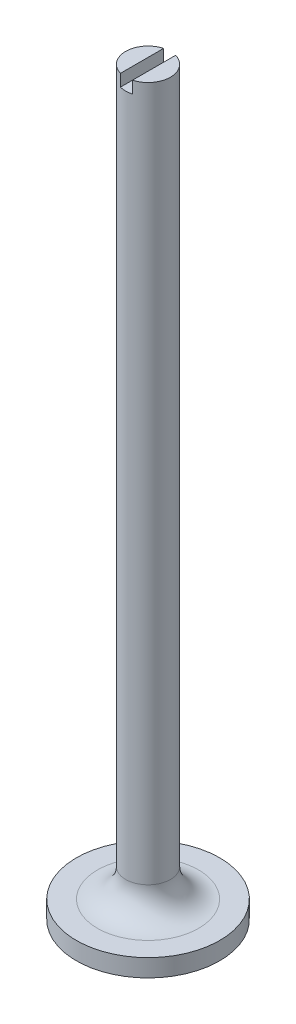
SolidWorks part; units mm, degrees
material "AISI 316 Annealed Stainless Steel Bar (SS)"
ref_plane "Front Plane" through (0, 0, 0) normal (0, 0, 1) x (1, 0, 0)
ref_plane "Top Plane" through (0, 0, 0) normal (0, 1, 0) x (1, 0, 0)
ref_plane "Right Plane" through (0, 0, 0) normal (1, 0, 0) x (0, 0, -1)
sketch "Sketch1" plane through (0, 0, 0) normal (0, 0, 1) x (1, 0, 0)
  line L0 (0, -31.8317) -> (0, 0) construction
  line L1 (0, 0) -> (10.16, 0)
  line L2 (10.16, 0) -> (10.16, 2.5)
  line L4 (3.175, 2.5) -> (3.175, 105)
  line L5 (3.175, 105) -> (0, 105)
  line L7 (0, 105) -> (0, 0)
  line L8 (10.16, 2.5) -> (3.175, 2.5)
  dimension "D1" = 10.16
  dimension "D2" = 3.175
  dimension "D3" = 2.5
  dimension "D4" = 105
revolve "Revolve1" add sketch "Sketch1" angle 360 about L0
cosmetic thread "Cosmetic Thread1" parameters "D1"=12, "D2"=5.268
sketch "Sketch2" [suppressed] plane through (0, 2.5, 0) normal (0, 1, 0) x (1, 0, 0)
  line L0 (-0.75, 10.1323) -> (-0.75, 0)
  line L1 (-0.75, 0) -> (0.75, 0)
  line L2 (0.75, 0) -> (0.75, 10.1323)
  circle A0 centre (0, 0) radius 10.16 construction
  arc A1 (0.75, 10.1323) -> (-0.75, 10.1323) centre (0, 0) ccw
  point P7 (0, 0)
  dimension "D1" = 1.5
extrude "Boss-Extrude1" [suppressed] add sketch "Sketch2" along normal blind 12
pattern_circular "CirPattern1" [suppressed] count 3 over 360
sketch "Sketch3" [suppressed] plane through (0, 14.5, 0) normal (0, 1, 0) x (1, 0, 0)
  circle A0 centre (0, 0) radius 7.475
  dimension "D1" = 14.95
extrude "Cut-Extrude2" [suppressed] cut sketch "Sketch3" against normal up to surface (12 mm away) flip side to cut
fillet "Fillet1" radius 4 1 edges at (0, 2.5, -3.175)
sketch "Sketch4" plane through (0, 0, 0) normal (0, 0, 1) x (1, 0, 0)
  line L0 (3.175, 105) -> (-3.175, 105) construction
  line L1 (-0.85, 105) -> (0.85, 105)
  line L2 (-0.85, 105) -> (-0.85, 103.3)
  line L3 (-0.85, 103.3) -> (0.85, 103.3)
  line L4 (0.85, 105) -> (0.85, 103.3)
  line L5 (0, 103.3) -> (0, 0) construction
  dimension "D1" = 1.7
  dimension "D2" = 1.7
extrude "Cut-Extrude3" cut sketch "Sketch4" against normal through all both and the other way through all
hole_wizard "1/16 (0.0625) Dowel Hole1" positions "Sketch5" profile "Sketch6" hole size "1/16" standard "ANSI Inch"
sketch "Sketch5" [suppressed] plane through (0, 0, 0) normal (0, -1, 0) x (-1, 0, 0)
  point P0 (5.675, -6.7648)
  point P3 (-5.675, 6.7648)
sketch "Sketch6" [suppressed] plane through (-5.675, 0, 6.7648) normal (1, 0, 0) x (0, 0, -1)
  line L0 (0, 0) -> (0, 6.4769)
  line L1 (0, 6.4769) -> (0.7937, 6)
  line L2 (0.7937, 6) -> (0.7937, 0)
  line L5 (0.7937, 0) -> (0, 0)
  line L10 (0, 6.4769) -> (-0.7937, 6) construction
  line L11 (0, -6.35) -> (0, 107.95) construction
  dimension "Hole Dia." = 1.5875
  dimension "Hole Depth" = 6
  dimension "Drill Angle" = 118
